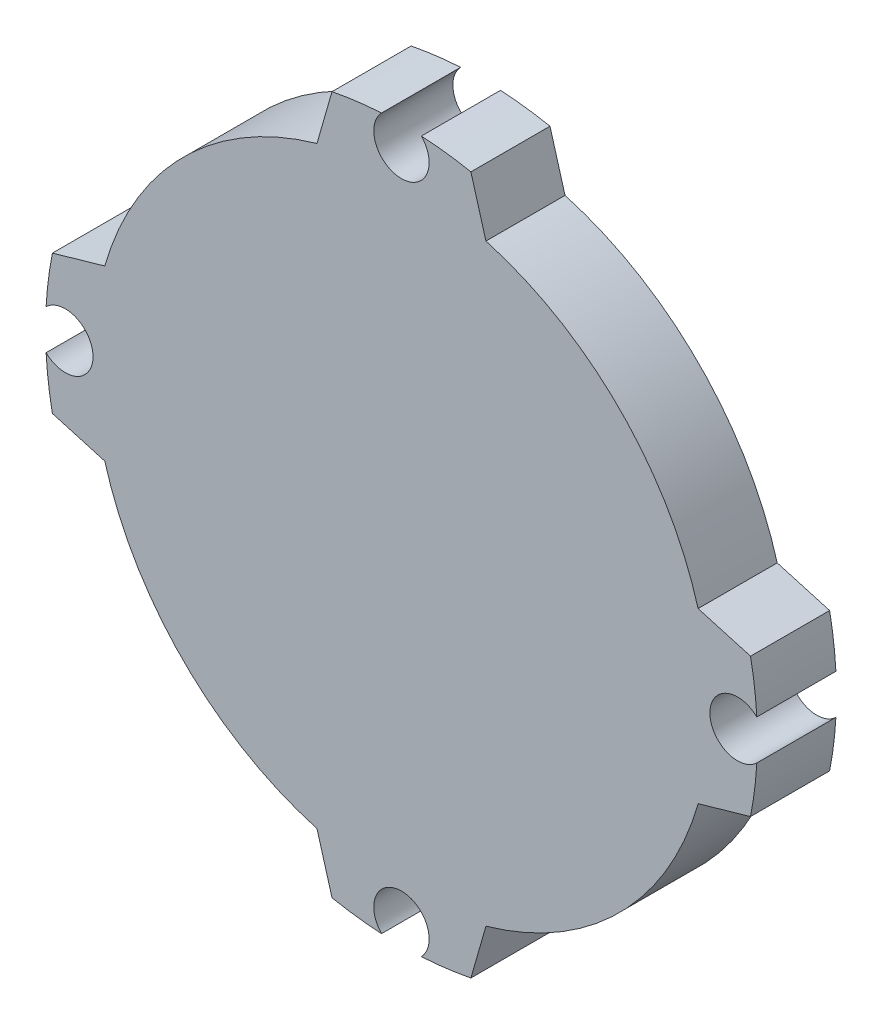
SolidWorks part; units mm, degrees
ref_plane "Front Plane" through (0, 0, 0) normal (0, 0, 1) x (1, 0, 0)
ref_plane "Top Plane" through (0, 0, 0) normal (0, 1, 0) x (1, 0, 0)
ref_plane "Right Plane" through (0, 0, 0) normal (1, 0, 0) x (0, 0, -1)
sketch "Sketch1" plane through (0, 0, 0) normal (0, 0, 1) x (1, 0, 0)
  line L0 (-11.755, 49.6875) -> (-12.6702, 46.4982)
  line L1 (-8.3973, 48.4947) -> (-8.3973, 54.2267) construction
  line L2 (-5.0396, 49.6875) -> (-4.1244, 46.4982)
  line L3 (9.7955, 34.8524) -> (6.6061, 35.7676)
  line L4 (9.7955, 28.1371) -> (6.6061, 27.2219)
  line L5 (-5.0396, 13.302) -> (-4.1244, 16.4913)
  line L6 (-11.755, 13.302) -> (-12.6702, 16.4913)
  line L7 (-26.59, 28.1371) -> (-23.4007, 27.2219)
  line L8 (-26.59, 34.8524) -> (-23.4007, 35.7676)
  arc A1 (-23.4007, 27.2219) -> (-12.6702, 16.4913) centre (-8.3973, 31.4947) ccw
  arc A2 (-26.59, 34.8524) -> (-26.59, 28.1371) centre (-8.3973, 31.4947) ccw
  arc A3 (-8.3973, 49.8947) -> (-7.8582, 49.7868) centre (-8.3973, 48.4947) ccw
  circle A7 centre (-8.3973, 14.4947) radius 1.4
  circle A8 centre (8.6027, 31.4947) radius 1.4
  circle A9 centre (-25.3973, 31.4947) radius 1.4
  arc A10 (-8.3973, 49.9947) -> (-11.755, 49.6875) centre (-8.3973, 31.4947) ccw
  arc A11 (9.7955, 28.1371) -> (9.7955, 34.8524) centre (-8.3973, 31.4947) ccw
  arc A12 (-11.755, 13.302) -> (-5.0396, 13.302) centre (-8.3973, 31.4947) ccw
  arc A13 (-26.375, 34.9141) -> (-26.375, 28.0754) centre (-8.3973, 31.4947) ccw
  arc A14 (-11.8167, 13.517) -> (-11.8167, 49.4724) centre (-8.3973, 31.4947) ccw
  arc A15 (6.6061, 35.7676) -> (-4.1244, 46.4982) centre (-8.3973, 31.4947) ccw
  arc A16 (-4.1244, 16.4913) -> (6.6061, 27.2219) centre (-8.3973, 31.4947) ccw
  arc A17 (-12.6702, 46.4982) -> (-23.4007, 35.7676) centre (-8.3973, 31.4947) ccw
  circle A18 centre (-8.3973, 31.4947) radius 18
  point P31 (-8.3973, 31.4947)
  dimension "D1" = 4
extrude "Boss-Extrude1" add sketch "Sketch1" along normal blind 4 contours L0 A17 L8 A13 A9 L7 A1 L6 A14 A7 L5 A16 L4 A8 L3 A15 L2 A3
